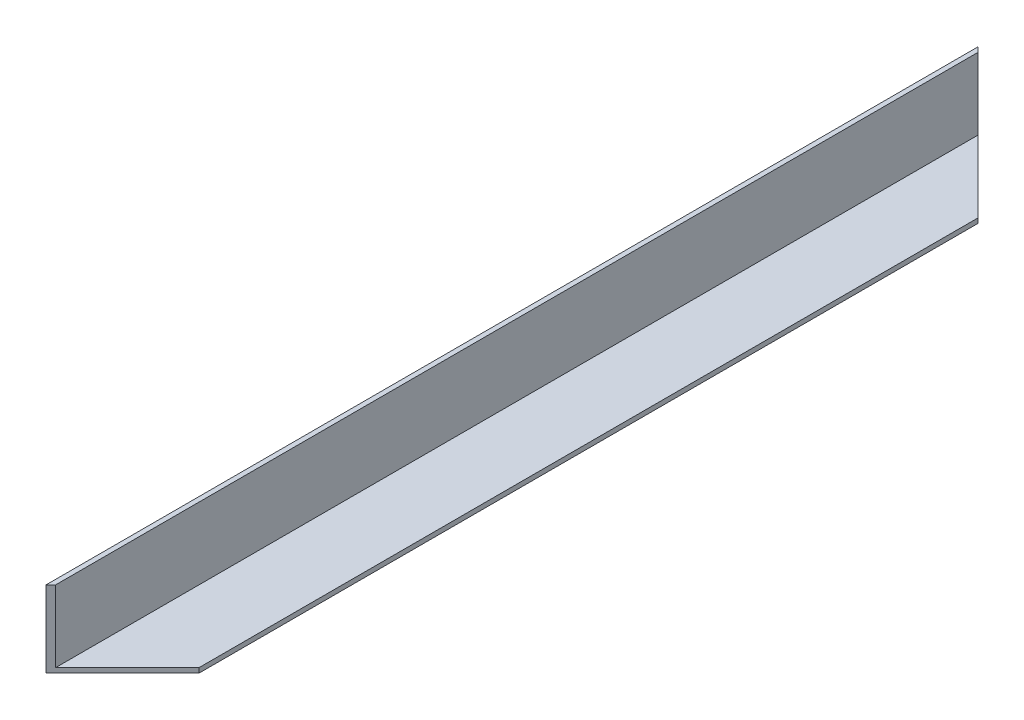
SolidWorks part; units mm, degrees
ref_plane "Front Plane" through (0, 0, 0) normal (0, 0, 1) x (1, 0, 0)
ref_plane "Top Plane" through (0, 0, 0) normal (0, 1, 0) x (1, 0, 0)
ref_plane "Right Plane" through (0, 0, 0) normal (1, 0, 0) x (0, 0, -1)
sketch "Sketch1" plane through (0, 0, 0) normal (0, 0, 1) x (1, 0, 0)
  line L0 (0, 0) -> (0, 30)
  line L1 (0, 0) -> (30, 0)
extrude "Extrude-Thin1" add sketch "Sketch1" along normal blind 390 thin thin type one direction wall 2
sketch "Sketch2" plane through (0, -2, 0) normal (0, -1, 0) x (1, 0, 0)
  line L0 (-2, 0) -> (30, 32)
  line L1 (30, 390) -> (30, 0) construction
  line L2 (30, 32) -> (30, 0)
  line L3 (30, 0) -> (-2, 0)
  line L4 (30, 195) -> (146.7425, 195) construction
  line L5 (30, 358) -> (30, 390)
  line L6 (-2, 390) -> (30, 358)
  line L7 (30, 390) -> (-2, 390)
extrude "Cut-Extrude1" cut sketch "Sketch2" against normal through all
